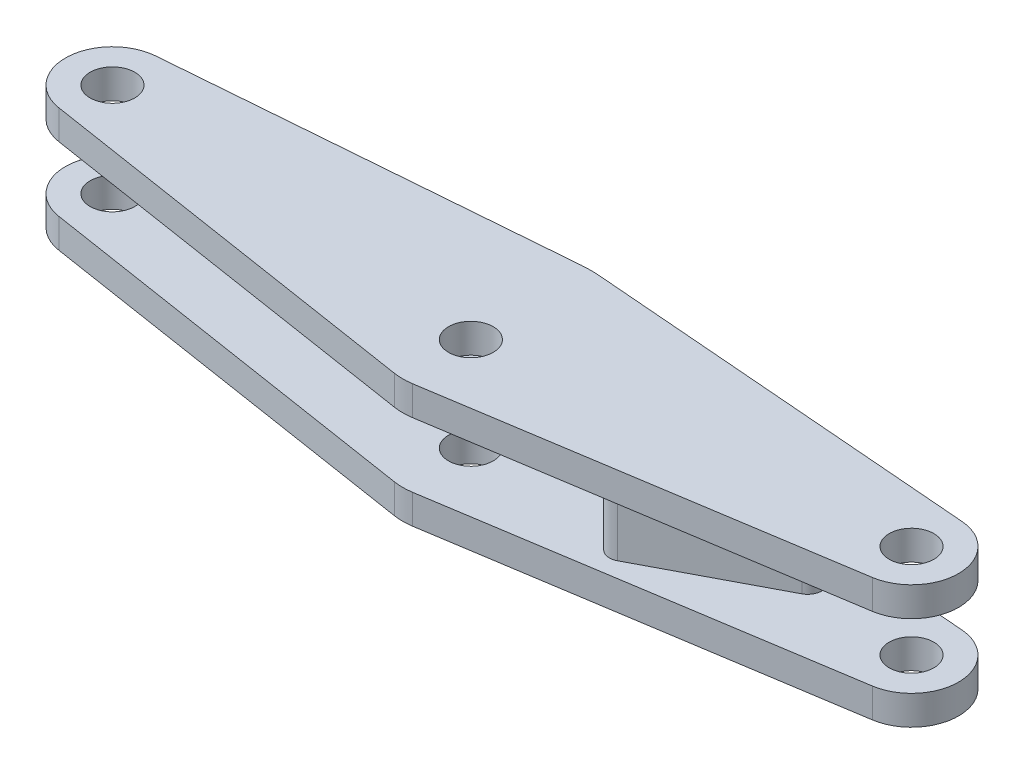
SolidWorks part; units mm, degrees
ref_plane "Front Plane" through (0, 0, 0) normal (0, 0, 1) x (1, 0, 0)
ref_plane "Top Plane" through (0, 0, 0) normal (0, 1, 0) x (1, 0, 0)
ref_plane "Right Plane" through (0, 0, 0) normal (1, 0, 0) x (0, 0, -1)
sketch "Sketch1" plane through (0, 0, 0) normal (0, 1, 0) x (1, 0, 0)
  line L0 (-17, 0) -> (17, 0) construction
  line L1 (-17.1594, 1.9936) -> (-0.3986, 3.3341)
  line L2 (0, -4.65) -> (0, 3.35) construction
  line L3 (-17.3087, -1.976) -> (-0.3859, -4.62)
  line L4 (0.3986, 3.3341) -> (17.1594, 1.9936)
  line L5 (0.3859, -4.62) -> (17.3087, -1.976)
  circle A0 centre (-17, 0) radius 0.95
  arc A1 (-17.1594, 1.9936) -> (-17.3087, -1.976) centre (-17, 0) ccw
  circle A2 centre (17, 0) radius 0.95
  arc A3 (17.3087, -1.976) -> (17.1594, 1.9936) centre (17, 0) ccw
  arc A4 (0.3986, 3.3341) -> (-0.3986, 3.3341) centre (0, -1.65) ccw
  arc A5 (-0.3859, -4.62) -> (0.3859, -4.62) centre (0, -2.15) ccw
  circle A6 centre (0, -1.75) radius 0.95
  point P17 (0, -4.65)
  point P20 (0, 0)
  point P21 (0, -3.3344)
  point P22 (0, 0)
  point P23 (0, 0)
  point P24 (0, -4.65)
  point P25 (0, -3.3344)
  point P26 (0, -3.3344)
  point P27 (0, -3.3344)
  point P28 (0, -4.1922)
  point P29 (0, -4.65)
  point P30 (0, 0)
  point P31 (0, 0)
  dimension "D4" = 1.9
  dimension "D5" = 4
  dimension "D6" = 4
  dimension "D7" = 1.9
  dimension "D8" = 5
  dimension "D9" = 2.5
  dimension "D11" = 1.9
  dimension "D1" = 34
  dimension "D2" = 8
  dimension "D3" = 3.35
  dimension "D10" = 1.75
extrude "Boss-Extrude1" add sketch "Sketch1" along normal mid plane 5.25
sketch "Sketch3" plane through (0, 0, 0) normal (0, 0, 1) x (1, 0, 0)
  line L0 (19, -2.625) -> (19, 2.625) construction
  line L1 (-19, 1.375) -> (19, 1.375)
  line L2 (-19, 1.375) -> (-19, -1.375)
  line L3 (-19, -1.375) -> (19, -1.375)
  line L4 (19, 1.375) -> (19, -1.375)
  line L5 (-19, 1.375) -> (19, -1.375) construction
  line L6 (-19, -1.375) -> (19, 1.375) construction
  line L7 (-16.05, 2.625) -> (-17.95, 2.625) construction
  line L8 (-19, -2.625) -> (-17.1594, -2.625) construction
  point P0 (0, 0)
  dimension "D1" = 1.25
  dimension "D2" = 1.25
extrude "Cut-Extrude1" cut sketch "Sketch3" against normal through all both and the other way through all
sketch "Sketch4" plane through (0, 0, 0) normal (0, 1, 0) x (1, 0, 0)
  line L0 (0, 0) -> (15.4613, 0) construction
  line L1 (3.4057, 0.45) -> (12.1332, 0.45) construction
  line L2 (7, -2.25) -> (12.1332, 0.45) construction
  line L3 (6.7207, -1.719) -> (11.8539, 0.981)
  line L4 (7.2793, -2.781) -> (12.4125, -0.081)
  arc A0 (6.7207, -1.719) -> (7.2793, -2.781) centre (7, -2.25) ccw
  arc A1 (12.4125, -0.081) -> (11.8539, 0.981) centre (12.1332, 0.45) ccw
  point P6 (9.5666, -0.9)
  point P11 (15.4613, -0.081)
  dimension "D4" = 0.6
  dimension "D1" = 5.8
  dimension "D2" = 0.45
  dimension "D3" = 2.25
  dimension "D5" = 7
extrude "Boss-Extrude2" add sketch "Sketch4" along normal up to next (2.625 mm away) and the other way up to next (1.375 mm away)
